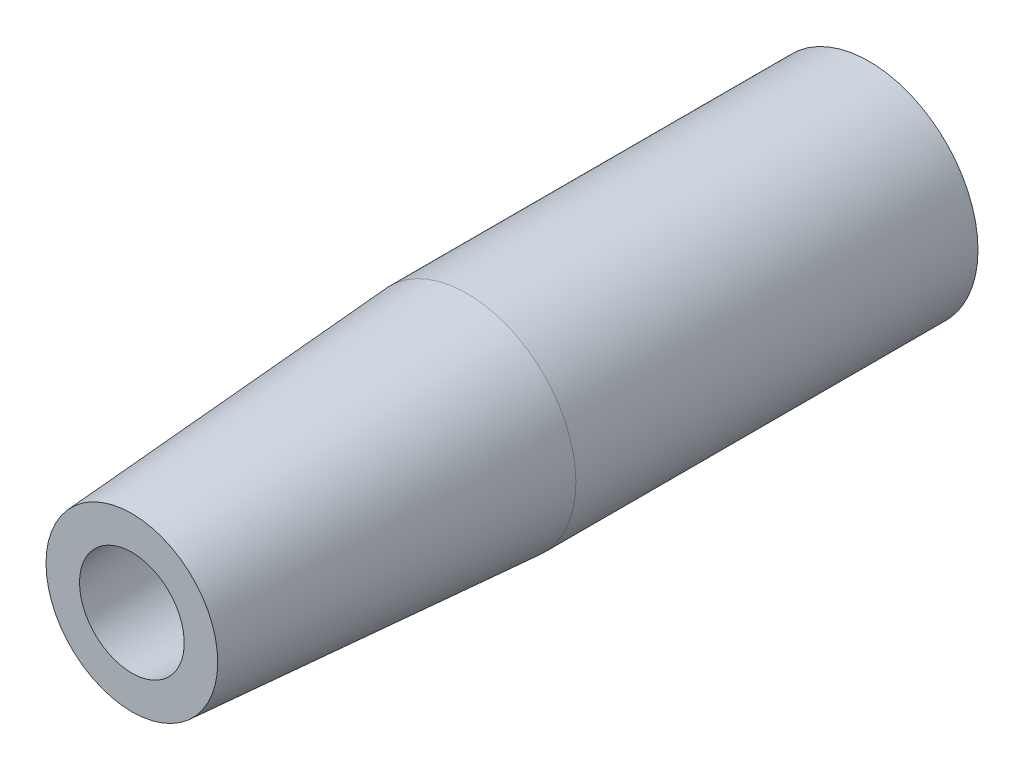
SolidWorks part; units mm, degrees
ref_plane "Front Plane" through (0, 0, 0) normal (0, 0, 1) x (1, 0, 0)
ref_plane "Top Plane" through (0, 0, 0) normal (0, 1, 0) x (1, 0, 0)
ref_plane "Right Plane" through (0, 0, 0) normal (1, 0, 0) x (0, 0, -1)
sketch "Sketch1" plane through (0, 0, 0) normal (0, 0, 1) x (1, 0, 0)
  circle A0 centre (0, 0) radius 22.5
  circle A1 centre (0, 0) radius 32.5
  dimension "D1" = 45
  dimension "D2" = 65
extrude "Boss-Extrude1" add sketch "Sketch1" along normal blind 120
sketch "Sketch6" plane through (0, 0, 0) normal (0, 1, 0) x (1, 0, 0)
  line L0 (0, 116.2006) -> (0, -633.8568) construction
sketch "Sketch8" plane through (0, 0, 0) normal (1, 0, 0) x (0, 0, -1)
  line L0 (-120, 32.5) -> (-220, 25.625)
  line L1 (-120, 22.5) -> (-220, 15.625)
  line L2 (116.2006, 0) -> (-633.8568, 0) construction
  line L3 (-120, 22.5) -> (-120, -22.5) construction
  line L5 (-220, 15.625) -> (-220, 25.625)
  line L6 (-120, 22.5) -> (-120, 32.5)
  dimension "D1" = 15.625
  dimension "D2" = 25.625
  dimension "D3" = 100
revolve "Revolve1" add sketch "Sketch8" angle 360 about L0
